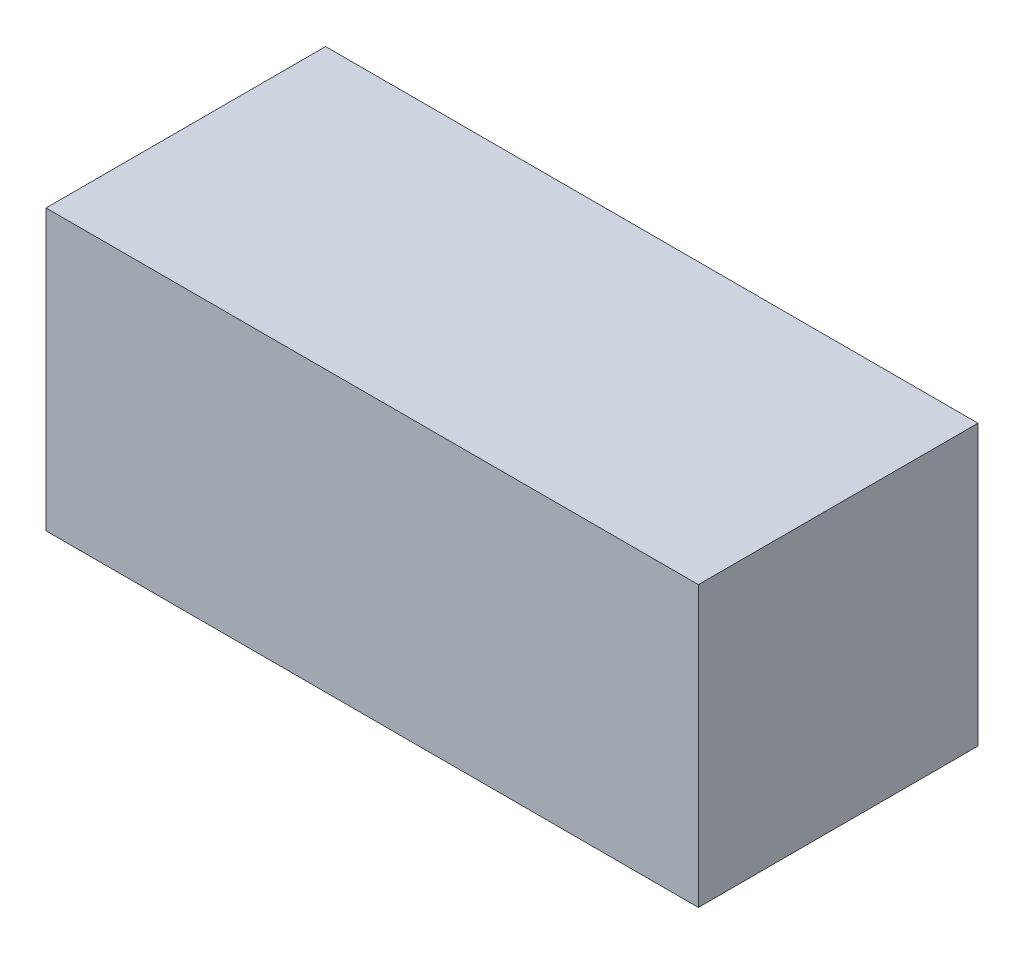
SolidWorks part; units mm, degrees
ref_plane "Front Plane" through (0, 0, 0) normal (0, 0, 1) x (1, 0, 0)
ref_plane "Top Plane" through (0, 0, 0) normal (0, 1, 0) x (1, 0, 0)
ref_plane "Right Plane" through (0, 0, 0) normal (1, 0, 0) x (0, 0, -1)
sketch "Sketch1" plane through (0, 0, 0) normal (0, 1, 0) x (1, 0, 0)
  line L1 (-35, -15) -> (35, -15)
  line L2 (-35, -15) -> (-35, 15)
  line L3 (-35, 15) -> (35, 15)
  line L4 (35, -15) -> (35, 15)
  line L5 (-35, -15) -> (35, 15) construction
  line L6 (-35, 15) -> (35, -15) construction
  point P0 (0, 0)
  dimension "D1" = 70
  dimension "D2" = 30
extrude "Boss-Extrude1" add sketch "Sketch1" along normal blind 30
equation "\"TrackerMass\"= 100'judges tracker mass"
equation "\"CargoMass\"= 250'mass of cargo"
equation "\"X2814MotorDiameter\"= 35mm'Outer diameter of X2814 motor"
equation "\"X2814MotorLength\"= 36mm'X2814 Motor lenght"
equation "\"X2814PadHeight\"= 2mm"
equation "\"X2814ShaftDiameter\"= 4mm"
equation "\"X2814ShaftLength\"= 16mm"
equation "\"X2814PadDiameter\"= 11mm"
equation "\"X2814PadHoleCircleDiameter\"= 15mm"
equation "\"X2814PadScrewDiameter\"= 2.5mm"
equation "\"X2814WireLength\"= 110mm"
equation "\"X2814ShaftHoleLargeCircleDiameter\"= 25mm"
equation "\"X2814ShaftHoleSmallCircleDiameter\"= 19mm"
equation "\"X2814ShaftScrewDiameter\"= 3mm"
equation "\"X2814PadScrewDepth\"= 3.5mm"
equation "\"X2814ShaftScrewDepth\"= 3mm"
equation "\"X2814BaseOffset\"= 10mm"
